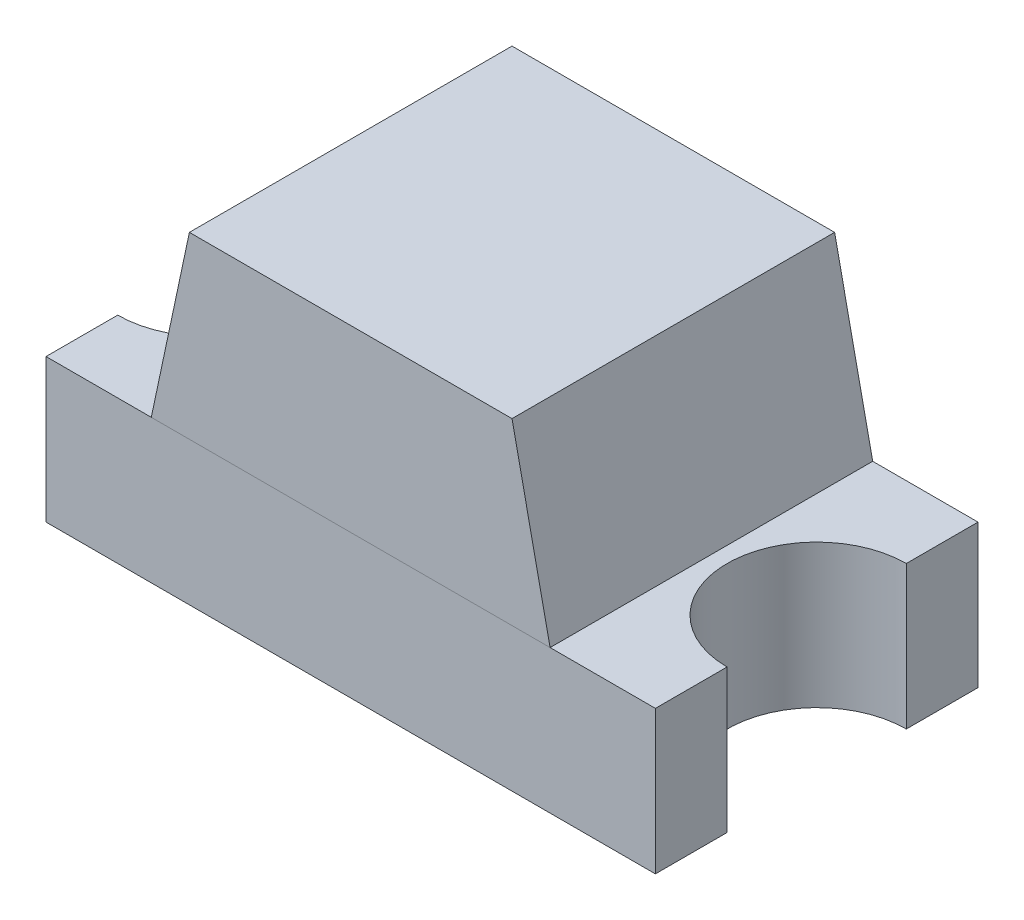
SolidWorks part; units mm, degrees
ref_plane "Front Plane" through (0, 0, 0) normal (0, 0, 1) x (1, 0, 0)
ref_plane "Top Plane" through (0, 0, 0) normal (0, 1, 0) x (1, 0, 0)
ref_plane "Right Plane" through (0, 0, 0) normal (1, 0, 0) x (0, 0, -1)
sketch "Sketch1" plane through (0, 0, 0) normal (0, 1, 0) x (1, 0, 0)
  line L0 (-0.85, -0.45) -> (0.85, -0.45)
  line L1 (-0.85, -0.45) -> (-0.85, -0.25)
  line L2 (0.85, -0.45) -> (0.85, -0.25)
  line L3 (-0.85, 0.45) -> (0.85, 0.45)
  line L4 (-0.85, -0.45) -> (0.85, 0.45) construction
  line L5 (0.85, -0.45) -> (-0.85, 0.45) construction
  line L6 (-0.85, 0.25) -> (-0.85, 0.45)
  line L7 (0.85, 0.25) -> (0.85, 0.45)
  arc A0 (-0.85, -0.25) -> (-0.85, 0.25) centre (-0.85, 0) ccw
  arc A1 (0.85, 0.25) -> (0.85, -0.25) centre (0.85, 0) ccw
  point P1 (0, 0)
  dimension "D1" = 1.7
  dimension "D2" = 0.9
extrude "Boss-Extrude1" add sketch "Sketch1" along normal blind 0.4
sketch "Sketch2" plane through (0, 0.4, 0) normal (0, 1, 0) x (1, 0, 0)
  line L0 (-0.45, -0.45) -> (0.45, -0.45)
  line L1 (-0.45, -0.45) -> (-0.45, 0.45)
  line L2 (0.45, -0.45) -> (0.45, 0.45)
  line L3 (-0.45, 0.45) -> (0.45, 0.45)
  line L4 (-0.45, -0.45) -> (0.45, 0.45) construction
  line L5 (0.45, -0.45) -> (-0.45, 0.45) construction
  line L6 (0.85, 0.45) -> (-0.85, 0.45) construction
  point P1 (0, 0)
  dimension "D1" = 0.9
extrude "Boss-Extrude2" add sketch "Sketch2" along normal blind 0.5 separate body
draft "Draft2" type of draft neutral plane draft angle 12 faces to draft 2 face at (-0.45, 0.65, 0) face at (0.45, 0.65, 0) neutral plane through (-0.45, 0.9, -0.45) neutral plane normal (0, 1, 0) parameters "D1"=12
